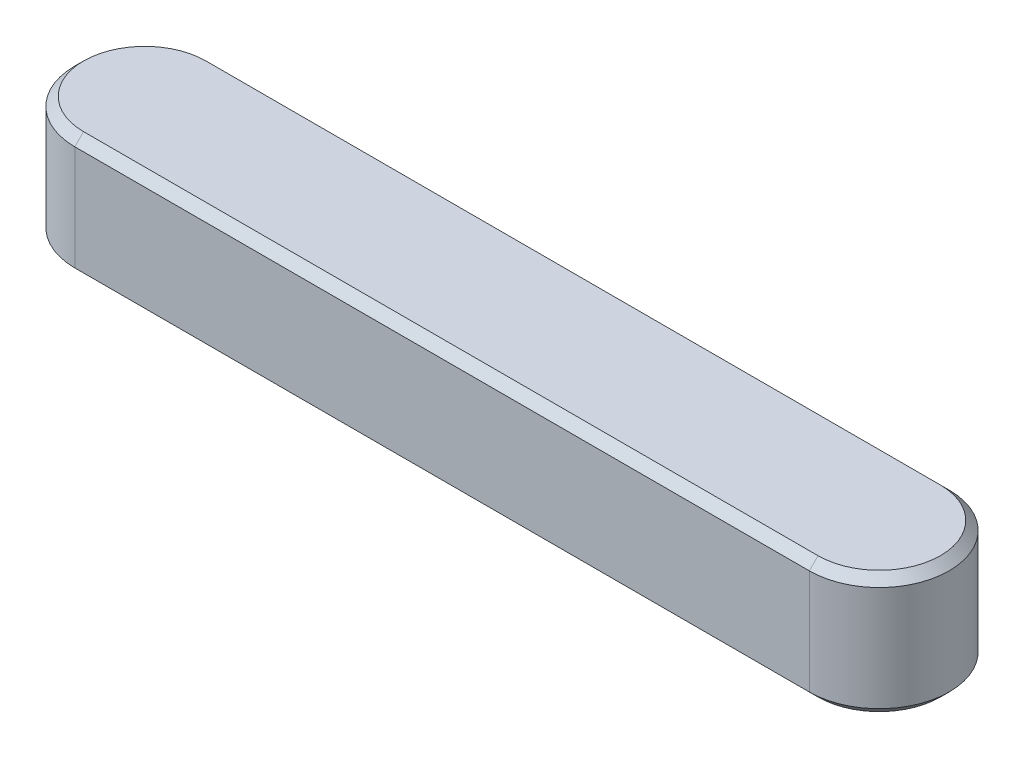
SolidWorks part; units mm, degrees
material "EN8"
ref_plane "Front Plane" through (0, 0, 0) normal (0, 0, 1) x (1, 0, 0)
ref_plane "Top Plane" through (0, 0, 0) normal (0, 1, 0) x (1, 0, 0)
ref_plane "Right Plane" through (0, 0, 0) normal (1, 0, 0) x (0, 0, -1)
sketch "Sketch1" plane through (0, 0, 0) normal (0, 1, 0) x (1, 0, 0)
  line L0 (-21, 0) -> (21, 0) construction
  line L7 (-21, 4) -> (21, 4)
  line L8 (-21, -4) -> (21, -4)
  arc A0 (-21, 4) -> (-21, -4) centre (-21, 0) ccw
  arc A1 (21, -4) -> (21, 4) centre (21, 0) ccw
  point P2 (0, 0)
  point P7 (-25, 0)
  point P8 (25, 0)
  dimension "D1" = 50
  dimension "D2" = 4
extrude "Boss-Extrude1" add sketch "Sketch1" along normal blind 7
chamfer "Chamfer1" distance 0.5 angle 45 8 edges at (0, 7, -4) (25, 7, 0) (0, 7, 4) (-25, 7, 0) (0, 0, 4) (25, 0, 0) (0, 0, -4) (-25, 0, 0)
